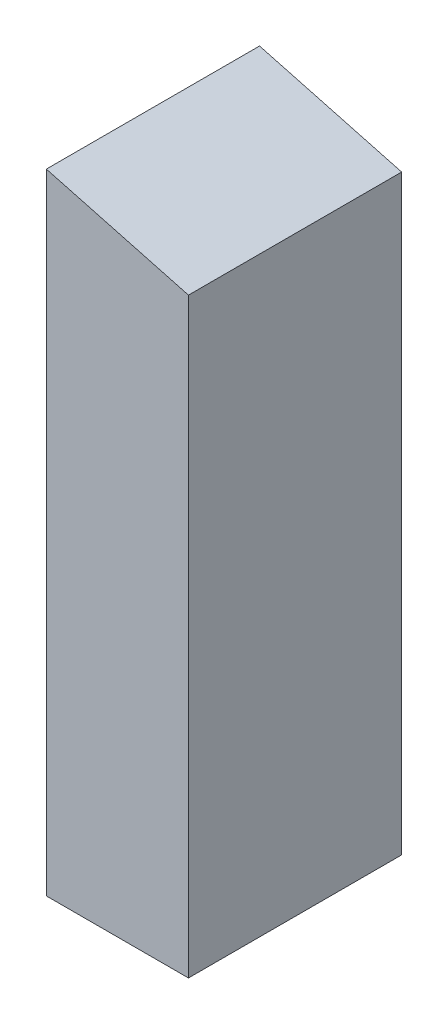
SolidWorks part; units mm, degrees
ref_plane "Alzado" through (0, 0, 0) normal (0, 0, 1) x (1, 0, 0)
ref_plane "Planta" through (0, 0, 0) normal (0, 1, 0) x (1, 0, 0)
ref_plane "Vista lateral" through (0, 0, 0) normal (1, 0, 0) x (0, 0, -1)
sketch "Croquis1" plane through (0, 0, 0) normal (0, 0, 1) x (1, 0, 0)
  line L0 (0, 0) -> (0, 225)
  line L1 (0, 225) -> (50.8, 211.3882)
  line L2 (0, 0) -> (50.8, 0)
  line L3 (50.8, 0) -> (50.8, 211.3882)
  dimension "D1" = 225
  dimension "D2" = 75
  dimension "D3" = 50.8
extrude "Saliente-Extruir1" add sketch "Croquis1" along normal blind 76.2
